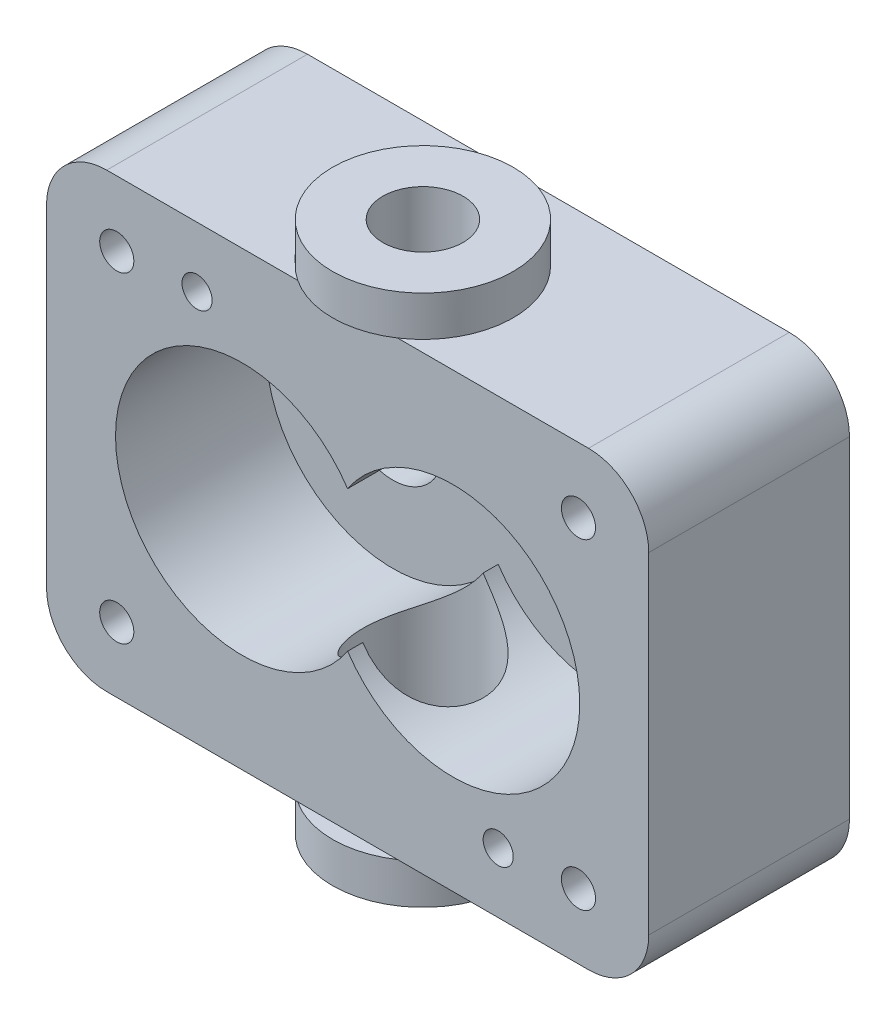
SolidWorks part; units mm, degrees
ref_plane "前视基准面" through (0, 0, 0) normal (0, 0, 1) x (1, 0, 0)
ref_plane "上视基准面" through (0, 0, 0) normal (0, 1, 0) x (1, 0, 0)
ref_plane "右视基准面" through (0, 0, 0) normal (1, 0, 0) x (0, 0, -1)
sketch "草图1" plane through (0, 0, 0) normal (0, 0, 1) x (1, 0, 0)
  line L0 (-48, -45) -> (48, -45)
  line L1 (60, -33) -> (60, 33)
  line L2 (48, 45) -> (-48, 45)
  line L3 (-60, 33) -> (-60, -33)
  arc A0 (-60, -33) -> (-48, -45) centre (-48, -33) ccw
  arc A1 (48, -45) -> (60, -33) centre (48, -33) ccw
  arc A2 (60, 33) -> (48, 45) centre (48, 33) ccw
  arc A3 (-48, 45) -> (-60, 33) centre (-48, 33) ccw
extrude "凸台-拉伸1" add sketch "草图1" along normal blind 40
ref_plane "基准面1" through (0, 45, 0) normal (0, 1, 0) x (1, 0, 0)
sketch "草图2" plane through (0, 45, 0) normal (0, 1, 0) x (1, 0, 0)
  circle A0 centre (0, -25) radius 18
extrude "凸台-拉伸2" add sketch "草图2" along normal blind 8
ref_plane "基准面2" through (0, -45, 0) normal (0, 1, 0) x (1, 0, 0)
sketch "草图3" plane through (0, -45, 0) normal (0, 1, 0) x (1, 0, 0)
  circle A0 centre (0, -25) radius 18
extrude "凸台-拉伸3" add sketch "草图3" against normal blind 8
ref_plane "基准面3" through (0, 0, 40) normal (0, 0, 1) x (1, 0, 0)
sketch "草图4" plane through (0, 0, 40) normal (0, 0, 1) x (1, 0, 0)
  circle A0 centre (-21, 0) radius 25.25
extrude "切除-拉伸1" cut sketch "草图4" against normal blind 30
sketch "草图5" plane through (0, 0, 40) normal (0, 0, 1) x (1, 0, 0)
  circle A0 centre (21, 0) radius 25.25
extrude "切除-拉伸2" cut sketch "草图5" against normal blind 30
ref_plane "基准面4" through (0, 0, 10) normal (0, 0, 1) x (1, 0, 0)
sketch "草图6" plane through (0, 0, 10) normal (0, 0, 1) x (1, 0, 0)
  circle A0 centre (-21, 0) radius 10
extrude "切除-拉伸3" cut sketch "草图6" against normal blind 10
sketch "草图7" plane through (0, 0, 10) normal (0, 0, 1) x (1, 0, 0)
  circle A0 centre (21, 0) radius 7.5
extrude "切除-拉伸4" cut sketch "草图7" against normal blind 8
ref_plane "基准面5" through (0, -53, 0) normal (0, 1, 0) x (1, 0, 0)
sketch "草图8" plane through (0, -53, 0) normal (0, 1, 0) x (1, 0, 0)
  circle A0 centre (0, -25) radius 12
extrude "切除-拉伸5" cut sketch "草图8" along normal blind 40
ref_plane "基准面6" through (0, 53, 0) normal (0, 1, 0) x (1, 0, 0)
sketch "草图9" plane through (0, 53, 0) normal (0, 1, 0) x (1, 0, 0)
  circle A0 centre (0, -25) radius 8
extrude "切除-拉伸6" cut sketch "草图9" against normal blind 40
sketch "草图10" plane through (0, 0, 40) normal (0, 0, 1) x (1, 0, 0)
  circle A0 centre (-46, 32) radius 3.4
  circle A1 centre (46, 32) radius 3.4
  circle A2 centre (-46, -32) radius 3.4
  circle A3 centre (46, -32) radius 3.4
extrude "切除-拉伸7" cut sketch "草图10" against normal blind 20
sketch "草图11" plane through (0, 0, 40) normal (0, 0, 1) x (1, 0, 0)
  circle A0 centre (-30, 33) radius 3
  circle A1 centre (30, -33) radius 3
extrude "切除-拉伸8" cut sketch "草图11" against normal blind 12
